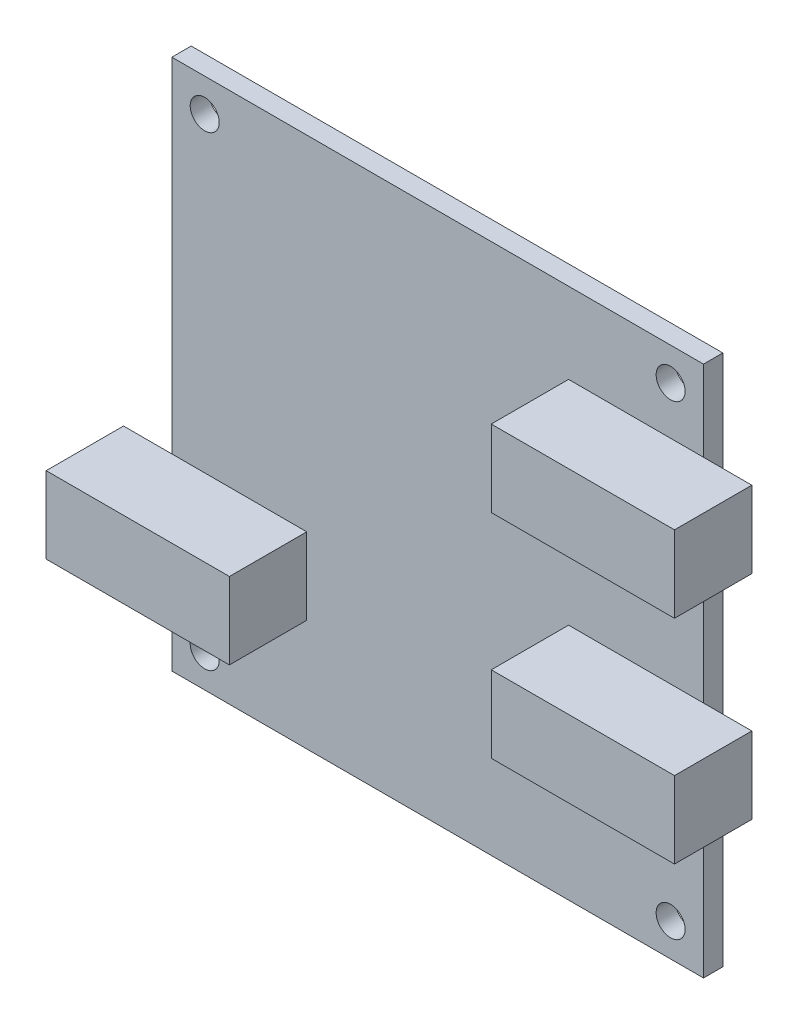
SolidWorks part; units mm, degrees
ref_plane "Ebene vorne" through (0, 0, 0) normal (1, 0, 0) x (0, 1, 0)
ref_plane "Ebene oben" through (0, 0, 0) normal (0, 0, 1) x (0, 1, 0)
ref_plane "Ebene rechts" through (0, 0, 0) normal (0, 1, 0) x (-1, 0, 0)
sketch "Skizze1" plane through (0, 0, 0) normal (0, 0, 1) x (0, 1, 0)
  line L1 (-27.5, -27.5) -> (27.5, -27.5)
  line L2 (-27.5, -27.5) -> (-27.5, 27.5)
  line L3 (-27.5, 27.5) -> (27.5, 27.5)
  line L4 (27.5, -27.5) -> (27.5, 27.5)
  line L5 (-27.5, -27.5) -> (27.5, 27.5) construction
  line L6 (-27.5, 27.5) -> (27.5, -27.5) construction
  point P0 (0, 0)
  dimension "D1" = 55
extrude "Aufsatz-Linear austragen1" add sketch "Skizze1" along normal blind 2
sketch "Skizze2" plane through (0, 0, 2) normal (0, 0, 1) x (1, 0, 0)
  line L12 (24.1, 24.1) -> (-24.1, 24.1)
  line L13 (-24.1, 24.1) -> (-24.1, -24.1)
  line L14 (-24.1, -24.1) -> (24.1, -24.1)
  line L15 (24.1, -24.1) -> (24.1, 24.1)
  line L16 (24.1, 24.1) -> (-24.1, 24.1) construction
  line L17 (-24.1, 24.1) -> (-24.1, -24.1) construction
  line L18 (-24.1, -24.1) -> (24.1, -24.1) construction
  line L19 (24.1, -24.1) -> (24.1, 24.1) construction
  circle A0 centre (24.1, 24.1) radius 1.5
  circle A1 centre (24.1, -24.1) radius 1.5
  circle A2 centre (-24.1, -24.1) radius 1.5
  circle A3 centre (-24.1, 24.1) radius 1.5
  dimension "D2" = 3
  dimension "D1" = 3.4
extrude "Schnitt-Linear austragen1" cut sketch "Skizze2" against normal blind 2
sketch "Skizze3" plane through (0, 0, 2) normal (0, 0, 1) x (1, 0, 0)
  line L0 (27.5, -27.5) -> (27.5, 27.5) construction
  line L1 (-32.5, -8.0457) -> (-13.5436, -8.0457)
  line L2 (-32.5, -8.0457) -> (-32.5, -15.9736)
  line L3 (-32.5, -15.9736) -> (-13.5436, -15.9736)
  line L4 (-13.5436, -8.0457) -> (-13.5436, -15.9736)
  line L5 (13.5436, 19.1526) -> (32.5, 19.1526)
  line L6 (13.5436, 19.1526) -> (13.5436, 11.2247)
  line L7 (13.5436, 11.2247) -> (32.5, 11.2247)
  line L8 (32.5, 19.1526) -> (32.5, 11.2247)
  line L9 (13.5436, -2.865) -> (32.5, -2.865)
  line L10 (13.5436, -2.865) -> (13.5436, -10.793)
  line L11 (13.5436, -10.793) -> (32.5, -10.793)
  line L12 (32.5, -2.865) -> (32.5, -10.793)
  line L13 (-27.5, 27.5) -> (-27.5, -27.5) construction
  point P12 (31.1033, -2.865)
  dimension "D1" = 5
  dimension "D2" = 5
extrude "Aufsatz-Linear austragen2" add sketch "Skizze3" along normal blind 8 separate body
